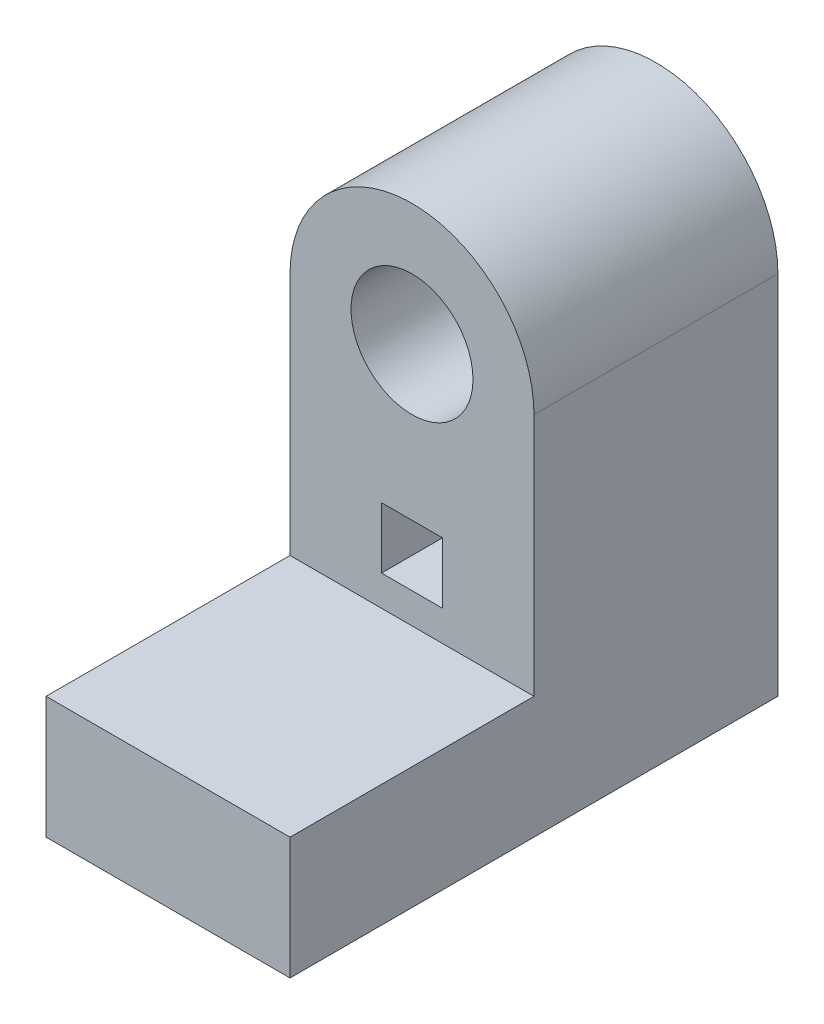
SolidWorks part; units mm, degrees
material "Brass"
ref_plane "Front Plane" through (0, 0, 0) normal (0, 0, 1) x (1, 0, 0)
ref_plane "Top Plane" through (0, 0, 0) normal (0, 1, 0) x (1, 0, 0)
ref_plane "Right Plane" through (0, 0, 0) normal (1, 0, 0) x (0, 0, -1)
sketch "Sketch2" plane through (0, 0, 0) normal (0, 0, 1) x (1, 0, 0)
  line L1 (50.8, 25.4) -> (50.8, 76.2)
  line L3 (0, 76.2) -> (0, 25.4)
  line L7 (50.8, 0) -> (0, 0)
  line L8 (0, 0) -> (0, 25.4)
  line L10 (50.8, 25.4) -> (50.8, 0)
  line L11 (19.05, 44.45) -> (31.75, 44.45)
  line L12 (19.05, 44.45) -> (19.05, 31.75)
  line L13 (19.05, 31.75) -> (31.75, 31.75)
  line L14 (31.75, 44.45) -> (31.75, 31.75)
  line L15 (19.05, 44.45) -> (31.75, 31.75) construction
  line L16 (19.05, 31.75) -> (31.75, 44.45) construction
  arc A0 (50.8, 76.2) -> (0, 76.2) centre (25.4, 76.2) ccw
  circle A1 centre (25.4, 76.2) radius 12.7
  point P3 (25.4, 38.1)
  dimension "D1" = 25.4
  dimension "D2" = 25.4
  dimension "D3" = 25.4
  dimension "D4" = 12.7
  dimension "D5" = 12.7
  dimension "D6" = 6.35
  dimension "D7" = 50.8
extrude "Boss-Extrude1" add sketch "Sketch2" along normal blind 50.8
sketch "Sketch3" plane through (0, 0, 0) normal (0, 0, 1) x (1, 0, 0)
  line L0 (0, 0) -> (50.8, 0)
  line L1 (50.8, 0) -> (50.8, 25.4)
  line L2 (50.8, 25.4) -> (0, 25.4)
  line L3 (0, 25.4) -> (0, 0)
  point P3 (0, 0)
  point P6 (0, 0)
  dimension "D1" = 25.4
  dimension "D2" = 50.8
extrude "Boss-Extrude2" add sketch "Sketch3" along normal blind 101.6
